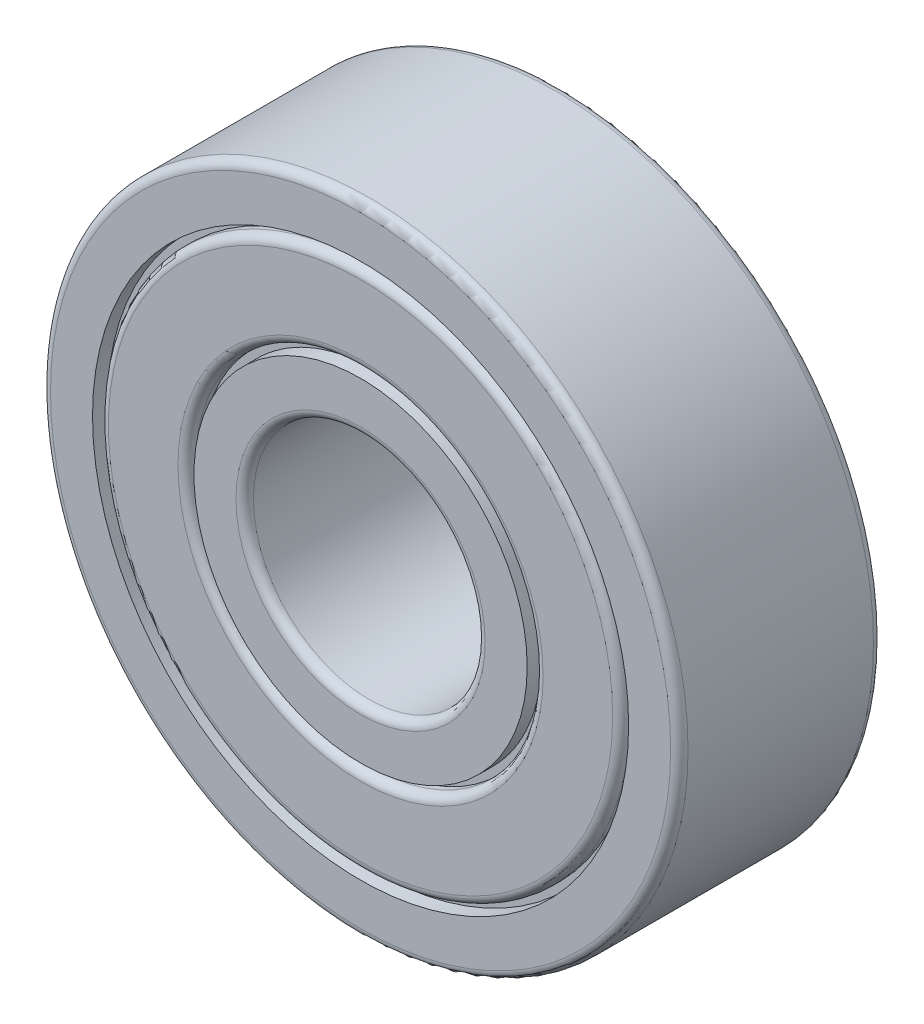
SolidWorks part; units mm, degrees
ref_plane "Front Plane" through (0, 0, 0) normal (0, 0, 1) x (1, 0, 0)
ref_plane "Top Plane" through (0, 0, 0) normal (0, 1, 0) x (1, 0, 0)
ref_plane "Right Plane" through (0, 0, 0) normal (1, 0, 0) x (0, 0, -1)
sketch "Sketch1" plane through (0, 0, 0) normal (0, 0, 1) x (1, 0, 0)
  circle A0 centre (0, 0) radius 11
  circle A1 centre (0, 0) radius 4
  dimension "D1" = 8
  dimension "D2" = 22
extrude "Boss-Extrude1" add sketch "Sketch1" along normal blind 7
fillet "Fillet1" radius 0.3 4 edges at (4, 0, 0) (11, 0, 0) (4, 0, 7) (11, 0, 7)
sketch "Sketch2" plane through (0, 0, 7) normal (0, 0, 1) x (1, 0, 0)
  line L0 (0, 4) -> (0, 11) construction
  line L1 (0, 9.25) -> (0, 5.75) construction
  circle A0 centre (0, 0) radius 4 construction
  circle A1 centre (0, 0) radius 11 construction
  circle A2 centre (0, 0) radius 5.75
  circle A3 centre (0, 0) radius 9.25
  point P7 (0, 7.5)
  point P10 (0, 7.5)
  dimension "D1" = 3.5
extrude "Cut-Extrude1" cut sketch "Sketch2" against normal through all
sketch "Sketch4" plane through (0, 0, 7) normal (0, 0, 1) x (1, 0, 0)
  line L0 (0, 9) -> (0, 6) construction
  line L1 (0, 4) -> (0, 11) construction
  circle A0 centre (0, 0) radius 4 construction
  circle A1 centre (0, 0) radius 11 construction
  circle A2 centre (0, 0) radius 6
  circle A3 centre (0, 0) radius 9
  point P3 (0, 7.5)
  point P11 (0, 7.5)
  dimension "D1" = 3
extrude "Boss-Extrude2" add sketch "Sketch4" against normal up to surface (7 mm away) separate body up to face at (9.25, 0, 0)
fillet "Fillet2" radius 0.3 2 edges at (6, 0, 7) (9, 0, 7)
sketch "Sketch5" plane through (0, 0, 0) normal (1, 0, 0) x (0, 0, -1)
  line L0 (0, 5.75) -> (0, 4.3)
  line L7 (-0.5, 9.25) -> (-6.5, 9.25)
  line L8 (-0.5, 9.25) -> (-0.5, 9)
  line L10 (0, 10.7) -> (0, 9.25)
  line L11 (0, -9.25) -> (0, -10.7)
  line L12 (0, -9.25) -> (0, -10.7) construction
  line L13 (0, 10.7) -> (0, 9.25) construction
  line L14 (0, 9) -> (0, 6)
  line L15 (0, -6) -> (0, -9)
  line L16 (0, -6) -> (0, -9) construction
  line L17 (0, 9) -> (0, 6) construction
  line L18 (-0.5, 9) -> (-6.5, 9)
  line L19 (-6.5, 9.25) -> (-6.5, 9)
  line L20 (0, -4.3) -> (0, -5.75)
  line L21 (0, -4.3) -> (0, -5.75) construction
  line L22 (0, 5.75) -> (0, 4.3) construction
  line L23 (-7, 10.7) -> (-7, -10.7) construction
  line L25 (-0.5, 6) -> (-6.5, 6)
  line L26 (-0.5, 6) -> (-0.5, 5.75)
  line L27 (-0.5, 5.75) -> (-6.5, 5.75)
  line L28 (-6.5, 6) -> (-6.5, 5.75)
  dimension "D1" = 0.5
  dimension "D2" = 0.5
ref_axis "Axis1" through (0, 0, -0.35) along (0, 0, 1)
revolve "Revolve2" add sketch "Sketch5" angle 360 about axis through (0, 0, -0.35) along (0, 0, 1)
